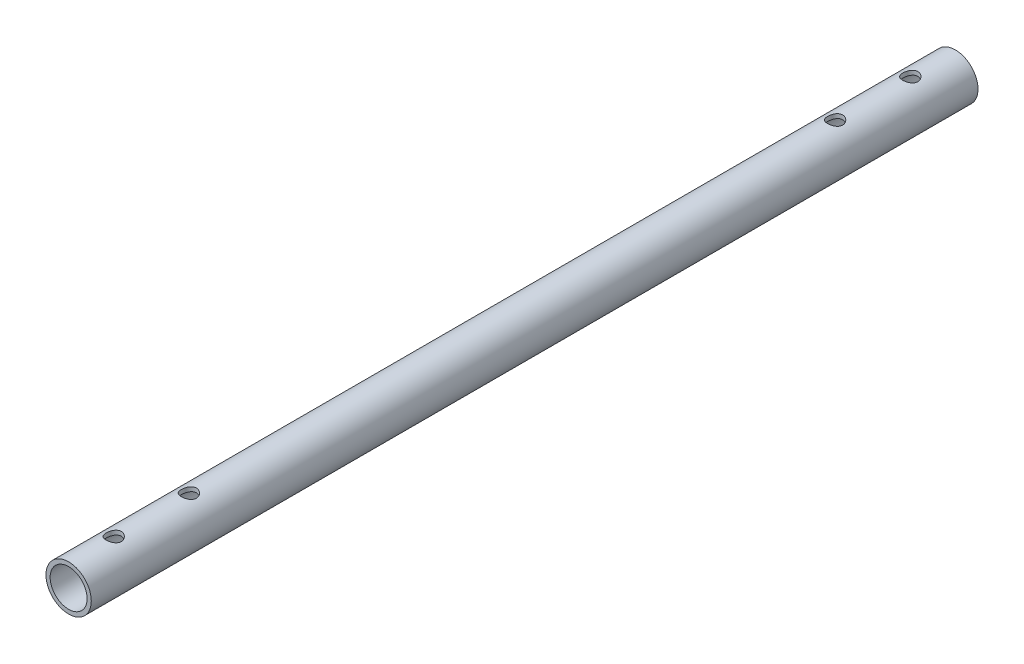
SolidWorks part; units mm, degrees
material "CK45"
ref_plane "Front Plane" through (0, 0, 0) normal (0, 0, 1) x (1, 0, 0)
ref_plane "Top Plane" through (0, 0, 0) normal (0, 1, 0) x (1, 0, 0)
ref_plane "Right Plane" through (0, 0, 0) normal (1, 0, 0) x (0, 0, -1)
sketch "Sketch1" plane through (0, 0, 0) normal (0, 0, 1) x (1, 0, 0)
  circle A0 centre (0, 0) radius 30.15
  dimension "D1" = 60.3
extrude "Extrude-Thin1" add sketch "Sketch1" along normal mid plane 1180 thin thin type one direction reverse wall 5.54
sketch "Sketch2" plane through (0, 0, 0) normal (0, 1, 0) x (1, 0, 0)
  line L0 (24.61, 590) -> (-24.61, 590) construction
  line L1 (0, 590) -> (0, 699.6614) construction
  line L2 (30.15, 590) -> (-30.15, 590) construction
  circle A0 centre (0, 530) radius 10.05
  circle A1 centre (0, 430) radius 10.05
  dimension "D1" = 20.1
  dimension "D2" = 60
  dimension "D3" = 100
extrude "Cut-Extrude1" cut sketch "Sketch2" against normal through all both and the other way through all
mirror "Mirror1" about plane through (0, 0, 0) normal (0, 0, 1) of "Cut-Extrude1"
